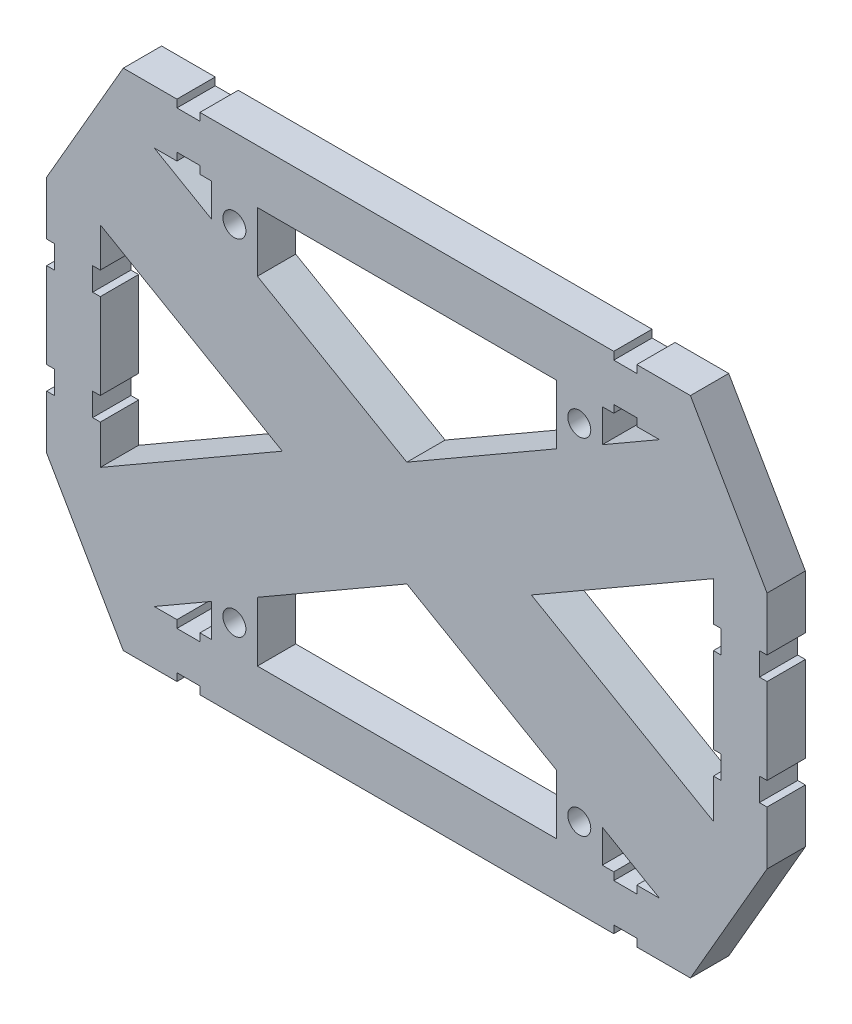
SolidWorks part; units mm, degrees
ref_plane "Plan de face" through (0, 0, 0) normal (0, 0, 1) x (1, 0, 0)
ref_plane "Plan de dessus" through (0, 0, 0) normal (0, 1, 0) x (1, 0, 0)
ref_plane "Plan de droite" through (0, 0, 0) normal (1, 0, 0) x (0, 0, -1)
sketch "Esquisse1" plane through (0, 0, 0) normal (0, 0, 1) x (1, 0, 0)
  line L0 (22, -30.0222) -> (-32, -30.0222)
  line L1 (-32, -30.0222) -> (-32, -29.0222)
  line L2 (-32, -29.0222) -> (-35, -29.0222)
  line L3 (-35, -29.0222) -> (-35, -30.0222)
  line L4 (-35, -30.0222) -> (-42, -30.0222)
  line L5 (-42, -30.0222) -> (-52, -12.7017)
  line L6 (-52, -12.7017) -> (-52, -5.7017)
  line L7 (-52, -5.7017) -> (-51, -5.7017)
  line L8 (-51, -5.7017) -> (-51, -2.7017)
  line L9 (-51, -2.7017) -> (-52, -2.7017)
  line L10 (-52, -2.7017) -> (-52, 8.4752)
  line L11 (-5, -30.0222) -> (-5, 35.7957) construction
  line L12 (35, 2.8868) -> (-45, 2.8868) construction
  line L13 (-47, -21.362) -> (-5, 2.8868) construction
  line L14 (-45, 8.4752) -> (-45, -2.7017)
  line L15 (-45, -2.7017) -> (-46, -2.7017)
  line L16 (-46, -2.7017) -> (-46, -5.7017)
  line L17 (-46, -5.7017) -> (-45, -5.7017)
  line L18 (-45, -5.7017) -> (-45, -10.8261)
  line L19 (35, 16.5996) -> (11.2487, 2.8868)
  line L20 (-37.9585, -23.0222) -> (-35, -23.0222)
  line L21 (-35, -23.0222) -> (-35, -24.0222)
  line L22 (-35, -24.0222) -> (-32, -24.0222)
  line L23 (-32, -24.0222) -> (-32, -23.0222)
  line L25 (-47, 27.1355) -> (-5, 2.8868) construction
  line L26 (14.5, -23.0222) -> (-5, -23.0222)
  line L27 (-32, 29.7957) -> (-32, 28.7957)
  line L28 (-35, 29.7957) -> (-32, 29.7957)
  line L29 (-35, 28.7957) -> (-35, 29.7957)
  line L30 (-37.9585, 28.7957) -> (-35, 28.7957)
  line L31 (-45, 16.5996) -> (-21.2487, 2.8868)
  line L32 (-45, 11.4752) -> (-45, 16.5996)
  line L33 (-46, 11.4752) -> (-45, 11.4752)
  line L34 (-46, 8.4752) -> (-46, 11.4752)
  line L35 (-45, 8.4752) -> (-46, 8.4752)
  line L36 (-51, 8.4752) -> (-52, 8.4752)
  line L37 (-51, 11.4752) -> (-51, 8.4752)
  line L38 (-52, 11.4752) -> (-51, 11.4752)
  line L39 (-52, 18.4752) -> (-52, 11.4752)
  line L40 (-42, 35.7957) -> (-52, 18.4752)
  line L41 (-35, 35.7957) -> (-42, 35.7957)
  line L42 (-35, 34.7957) -> (-35, 35.7957)
  line L43 (-32, 34.7957) -> (-35, 34.7957)
  line L44 (-32, 35.7957) -> (-32, 34.7957)
  line L45 (22, 35.7957) -> (-32, 35.7957)
  line L46 (37, 27.1355) -> (-5, 2.8868) construction
  line L47 (37, -21.362) -> (-5, 2.8868) construction
  line L48 (22, 35.7957) -> (22, 34.7957)
  line L49 (22, 34.7957) -> (25, 34.7957)
  line L50 (25, 34.7957) -> (25, 35.7957)
  line L51 (25, 35.7957) -> (32, 35.7957)
  line L52 (32, 35.7957) -> (42, 18.4752)
  line L53 (42, 18.4752) -> (42, 11.4752)
  line L54 (42, 11.4752) -> (41, 11.4752)
  line L55 (41, 11.4752) -> (41, 8.4752)
  line L56 (41, 8.4752) -> (42, 8.4752)
  line L57 (35, 8.4752) -> (36, 8.4752)
  line L58 (36, 8.4752) -> (36, 11.4752)
  line L59 (36, 11.4752) -> (35, 11.4752)
  line L60 (35, 11.4752) -> (35, 16.5996)
  line L61 (27.9585, 28.7957) -> (20.5, 24.4895)
  line L62 (27.9585, 28.7957) -> (25, 28.7957)
  line L63 (25, 28.7957) -> (25, 29.7957)
  line L64 (25, 29.7957) -> (22, 29.7957)
  line L65 (22, 29.7957) -> (22, 28.7957)
  line L66 (22, -24.0222) -> (22, -23.0222)
  line L67 (25, -24.0222) -> (22, -24.0222)
  line L68 (25, -23.0222) -> (25, -24.0222)
  line L69 (27.9585, -23.0222) -> (25, -23.0222)
  line L70 (-37.9585, 28.7957) -> (-30.5, 24.4895)
  line L71 (35, -5.7017) -> (35, -10.8261)
  line L72 (36, -5.7017) -> (35, -5.7017)
  line L73 (36, -2.7017) -> (36, -5.7017)
  line L74 (35, -2.7017) -> (36, -2.7017)
  line L75 (35, 8.4752) -> (35, -2.7017)
  line L76 (42, -2.7017) -> (42, 8.4752)
  line L77 (41, -2.7017) -> (42, -2.7017)
  line L78 (41, -5.7017) -> (41, -2.7017)
  line L79 (42, -5.7017) -> (41, -5.7017)
  line L80 (42, -12.7017) -> (42, -5.7017)
  line L81 (32, -30.0222) -> (42, -12.7017)
  line L82 (25, -30.0222) -> (32, -30.0222)
  line L83 (25, -29.0222) -> (25, -30.0222)
  line L84 (22, -29.0222) -> (25, -29.0222)
  line L85 (22, -30.0222) -> (22, -29.0222)
  line L86 (35, -10.8261) -> (11.2487, 2.8868)
  line L87 (-30.5, 28.7957) -> (-30.5, 24.4895)
  line L88 (-24.5, 28.7957) -> (-24.5, 21.0254)
  line L89 (-45, -10.8261) -> (-21.2487, 2.8868)
  line L90 (20.5, 28.7957) -> (20.5, 24.4895)
  line L91 (14.5, 28.7957) -> (14.5, 21.0254)
  line L92 (14.5, 21.0254) -> (-5, 9.7671)
  line L93 (-24.5, 21.0254) -> (-5, 9.7671)
  line L94 (-37.9585, -23.0222) -> (-30.5, -18.716)
  line L95 (-30.5, -23.0222) -> (-30.5, -18.716)
  line L96 (-24.5, -23.0222) -> (-24.5, -15.2519)
  line L97 (-24.5, -15.2519) -> (-5, -3.9936)
  line L98 (27.9585, -23.0222) -> (20.5, -18.716)
  line L99 (20.5, -23.0222) -> (20.5, -18.716)
  line L100 (14.5, -23.0222) -> (14.5, -15.2519)
  line L101 (14.5, -15.2519) -> (-5, -3.9936)
  line L102 (22, 28.7957) -> (20.5, 28.7957)
  line L103 (14.5, 28.7957) -> (-5, 28.7957)
  line L104 (-5, 28.7957) -> (-24.5, 28.7957)
  line L105 (-30.5, 28.7957) -> (-32, 28.7957)
  line L106 (-5, -23.0222) -> (-24.5, -23.0222)
  line L107 (-30.5, -23.0222) -> (-32, -23.0222)
  line L108 (22, -23.0222) -> (20.5, -23.0222)
  circle A0 centre (17.5, 25.3868) radius 1.5
  circle A1 centre (-27.5, 25.3868) radius 1.5
  circle A2 centre (17.5, -19.6132) radius 1.5
  circle A3 centre (-27.5, -19.6132) radius 1.5
  point P10 (-47, -21.362)
  point P41 (-52, 2.8868)
  point P73 (-5, 28.7957)
  point P74 (-5, -23.0222)
  point P75 (-5, -23.0222)
  point P94 (42, 2.8868)
  dimension "D13" = 2
  dimension "D1" = 1
  dimension "D2" = 3
  dimension "D3" = 7
  dimension "D4" = 3
  dimension "D5" = 7
  dimension "D6" = 60
  dimension "D7" = 90
  dimension "D8" = 1
  dimension "D9" = 1
  dimension "D10" = 1
  dimension "D11" = 7
  dimension "D12" = 3
  dimension "D14" = 20
  dimension "D15" = 30
  dimension "D16" = 2
  dimension "D17" = 22.5
  dimension "D18" = 22.5
  dimension "D19" = 3
extrude "Boss.-Extru.2" add sketch "Esquisse1" along normal blind 5
sketch "Esquisse4" plane through (0, 0, 0) normal (0, 0, -1) x (-1, 0, 0)
  line L1 (-17.5, 23.0296) -> (-15.4587, 24.2082)
  line L2 (-15.4587, 24.2082) -> (-15.4587, 26.5653)
  line L3 (-15.4587, 26.5653) -> (-17.5, 27.7439)
  line L4 (-17.5, 27.7439) -> (-19.5413, 26.5653)
  line L5 (-19.5413, 26.5653) -> (-19.5413, 24.2082)
  line L6 (-19.5413, 24.2082) -> (-17.5, 23.0296)
  line L7 (5, -32.2873) -> (5, 38.0608) construction
  line L8 (53.6304, 2.8868) -> (-43.6304, 2.8868) construction
  line L9 (5, -30.0222) -> (5, 35.7957) construction
  line L10 (-35, 2.8868) -> (45, 2.8868) construction
  line L11 (29.5413, 24.2082) -> (27.5, 23.0296)
  line L12 (29.5413, 26.5653) -> (29.5413, 24.2082)
  line L13 (27.5, 27.7439) -> (29.5413, 26.5653)
  line L14 (25.4587, 26.5653) -> (27.5, 27.7439)
  line L15 (25.4587, 24.2082) -> (25.4587, 26.5653)
  line L16 (27.5, 23.0296) -> (25.4587, 24.2082)
  line L17 (27.5, -17.2561) -> (25.4587, -18.4347)
  line L18 (25.4587, -18.4347) -> (25.4587, -20.7918)
  line L19 (25.4587, -20.7918) -> (27.5, -21.9704)
  line L20 (27.5, -21.9704) -> (29.5413, -20.7918)
  line L21 (29.5413, -20.7918) -> (29.5413, -18.4347)
  line L22 (29.5413, -18.4347) -> (27.5, -17.2561)
  line L23 (-19.5413, -18.4347) -> (-17.5, -17.2561)
  line L24 (-19.5413, -20.7918) -> (-19.5413, -18.4347)
  line L25 (-17.5, -21.9704) -> (-19.5413, -20.7918)
  line L26 (-15.4587, -20.7918) -> (-17.5, -21.9704)
  line L27 (-15.4587, -18.4347) -> (-15.4587, -20.7918)
  line L28 (-17.5, -17.2561) -> (-15.4587, -18.4347)
  circle A0 centre (-17.5, 25.3868) radius 2.0413 construction
  circle A1 centre (27.5, 25.3868) radius 2.0413 construction
  circle A2 centre (27.5, -19.6132) radius 2.0413 construction
  circle A3 centre (-17.5, -19.6132) radius 2.0413 construction
extrude "Enlèv. mat.-Extru.2" cut sketch "Esquisse4" against normal blind 2
